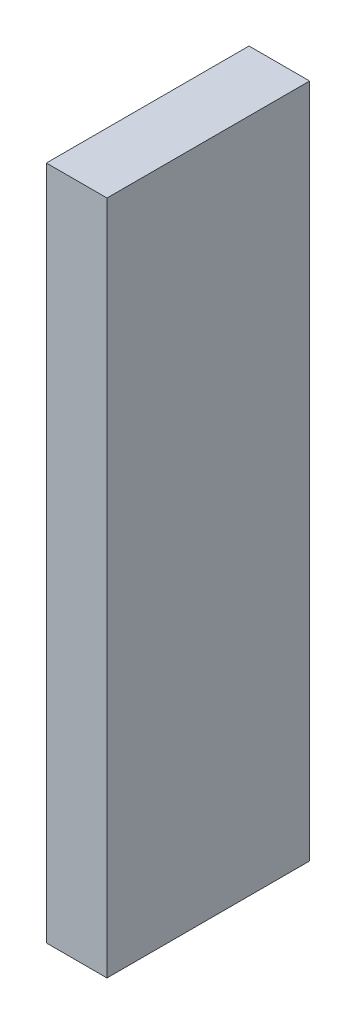
SolidWorks part; units mm, degrees
ref_plane "Plan de face" through (0, 0, 0) normal (0, 0, 1) x (1, 0, 0)
ref_plane "Plan de dessus" through (0, 0, 0) normal (0, 1, 0) x (1, 0, 0)
ref_plane "Plan de droite" through (0, 0, 0) normal (1, 0, 0) x (0, 0, -1)
sketch "Esquisse1" plane through (0, 0, 0) normal (0, 0, 1) x (1, 0, 0)
  text T0 "I" font "Century Gothic" height 5
extrude "Boss.-Extru.1" add sketch "Esquisse1" along normal blind 1.5
